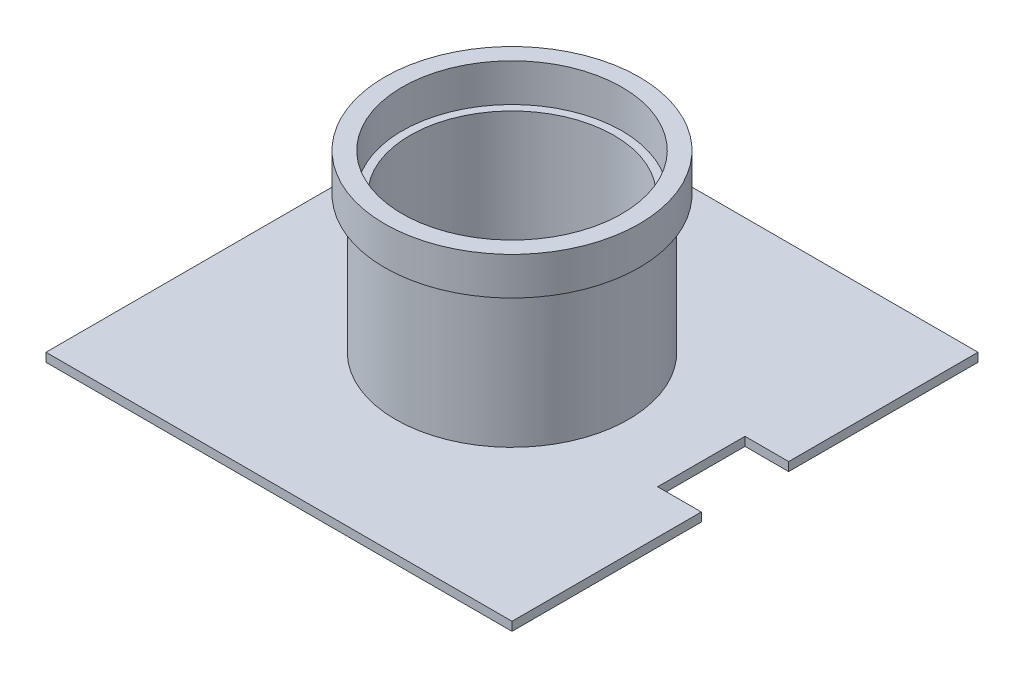
SolidWorks part; units mm, degrees
ref_plane "Alzado" through (0, 0, 0) normal (0, 0, 1) x (1, 0, 0)
ref_plane "Planta" through (0, 0, 0) normal (0, 1, 0) x (1, 0, 0)
ref_plane "Vista lateral" through (0, 0, 0) normal (1, 0, 0) x (0, 0, -1)
sketch "Croquis1" plane through (0, 0, 0) normal (0, 1, 0) x (1, 0, 0)
  circle A0 centre (0, 0) radius 37.7
  circle A1 centre (0, 0) radius 43.7
  dimension "D1" = 75.4
  dimension "D2" = 6
extrude "Saliente-Extruir1" add sketch "Croquis1" along normal blind 13
sketch "Croquis2" plane through (0, 0, 0) normal (0, -1, 0) x (1, 0, 0)
  circle A0 centre (0, 0) radius 35
  circle A1 centre (0, 0) radius 40
  dimension "D1" = 5
  dimension "D2" = 80
extrude "Saliente-Extruir2" add sketch "Croquis2" along normal blind 50
sketch "Croquis3" plane through (0, -50, 0) normal (0, -1, 0) x (1, 0, 0)
  line L0 (0, 0) -> (0, 80) construction
  line L1 (0, 80) -> (80, 80)
  line L2 (80, 80) -> (80, 15)
  line L3 (80, -80) -> (-80, -80)
  line L4 (0, 80) -> (-80, 80)
  line L5 (-80, 80) -> (-80, -80)
  line L6 (80, 0) -> (65, 0) construction
  line L7 (65, 0) -> (65, 15)
  line L8 (65, 0) -> (65, -15)
  line L9 (65, 15) -> (80, 15)
  line L10 (65, -15) -> (80, -15)
  line L11 (80, -15) -> (80, -80)
  circle A2 centre (0, 0) radius 35
  dimension "D1" = 80
  dimension "D2" = 80
  dimension "D3" = 160
  dimension "D4" = 160
  dimension "D5" = 15
  dimension "D6" = 15
  dimension "D7" = 15
extrude "Saliente-Extruir3" add sketch "Croquis3" against normal blind 3 separate body
sketch "Croquis4" plane through (0, -47, 0) normal (0, 1, 0) x (1, 0, 0)
  line L0 (0, 0) -> (0, -43.7) construction
  line L1 (0, -43.7) -> (0, -80) construction
  line L2 (80, -80) -> (-80, -80) construction
  line L3 (0, -61.85) -> (24.6146, -61.85) construction
  line L4 (0, 0) -> (0, 70.5685) construction
  circle A0 centre (0, 0) radius 43.7 construction
  circle A1 centre (0, 0) radius 61.85 construction
